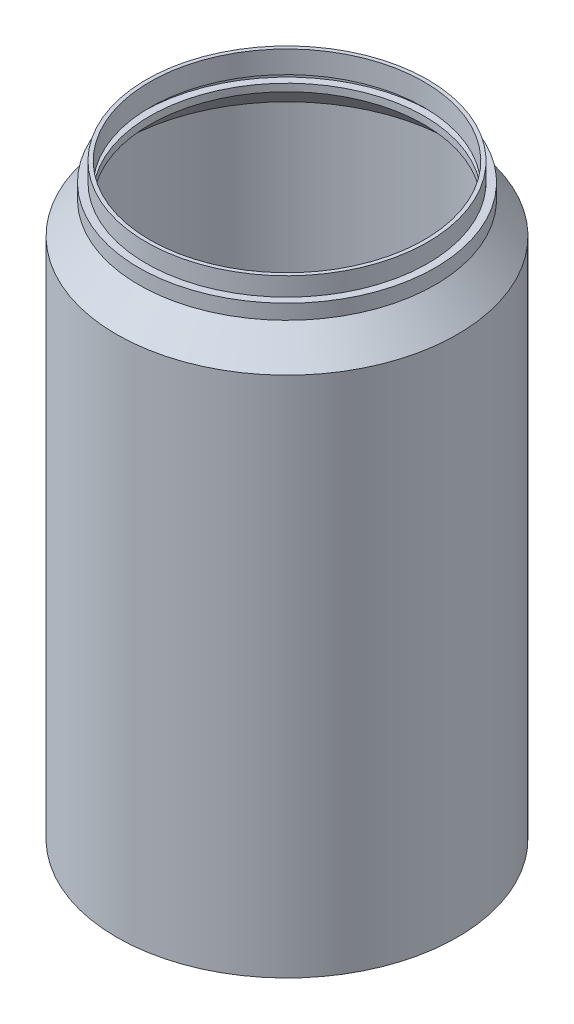
SolidWorks part; units mm, degrees
ref_plane "Front Plane" through (0, 0, 0) normal (0, 0, 1) x (1, 0, 0)
ref_plane "Top Plane" through (0, 0, 0) normal (0, 1, 0) x (1, 0, 0)
ref_plane "Right Plane" through (0, 0, 0) normal (1, 0, 0) x (0, 0, -1)
sketch "Sketch1" plane through (-3.3431, 93.1731, 24.269) normal (0, 0, 1) x (1, 0, 0)
  line L0 (3.3431, -93.1731) -> (3.3431, 145.2848) construction
  line L1 (-33.6569, 68.3279) -> (-33.6569, 62.3279)
  line L2 (-33.6569, 62.3279) -> (-35.6569, 62.3279)
  line L3 (-35.6569, 62.3279) -> (-35.6569, 60.3279)
  line L4 (-35.6569, 60.3279) -> (-33.6569, 60.3279)
  line L5 (-33.6569, 60.3279) -> (-33.6569, 58.3279)
  line L6 (-33.6569, 58.3279) -> (-41.6569, 50.3279)
  line L7 (-41.6569, 50.3279) -> (-41.6569, -89.6721)
  line L8 (-41.6569, -89.6721) -> (-33.6569, -95.2737)
  line L9 (-33.6569, -95.2737) -> (-28.6569, -95.2737)
  line L10 (-28.6569, -95.2737) -> (-25.6569, -93.1731)
  line L11 (-25.6569, -93.1731) -> (3.3431, -93.1731)
  point P10 (0, 0)
  point P15 (-28.2591, -60.5056)
  point P16 (-9.3168, -0.4163)
  point P17 (0, 0)
  point P18 (-28.0158, -68.4067)
  point P19 (-35.2844, 75.0609)
  point P21 (-35.2844, 59.9177)
  dimension "D1" = 5
  dimension "D2" = 145
  dimension "D3" = 145
  dimension "D4" = 3
  dimension "D5" = 8
  dimension "D6" = 45
  dimension "D7" = 2
  dimension "D8" = 2
  dimension "D9" = 2
  dimension "D10" = 8
  dimension "D11" = 6
  dimension "D12" = 140
  dimension "D13" = 45
revolve "Revolve-Thin1" add sketch "Sketch1" angle 360 about L0
